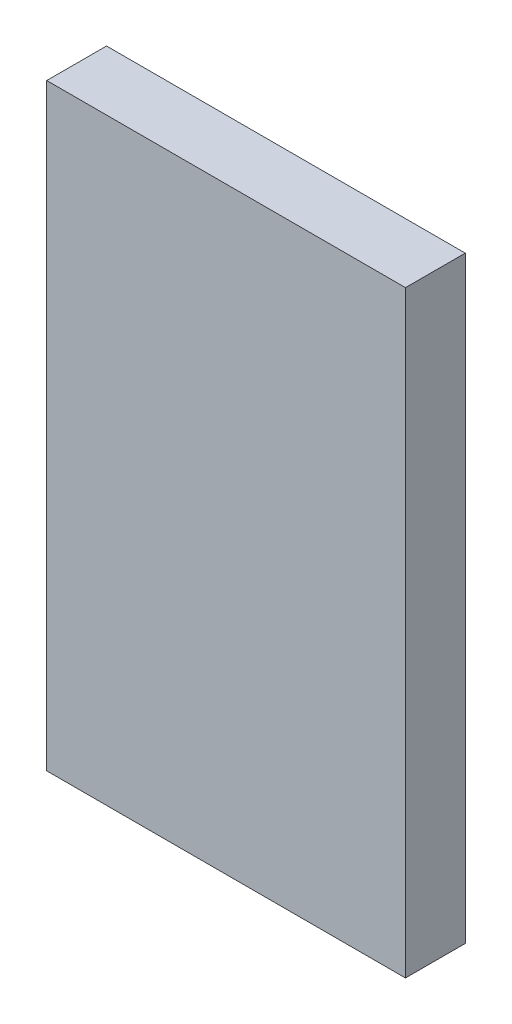
SolidWorks part; units mm, degrees
ref_plane "Спереди" through (0, 0, 0) normal (0, 0, 1) x (1, 0, 0)
ref_plane "Сверху" through (0, 0, 0) normal (0, 1, 0) x (1, 0, 0)
ref_plane "Справа" through (0, 0, 0) normal (1, 0, 0) x (0, 0, -1)
sketch "Эскиз1" plane through (0, 0, 0) normal (0, 0, 1) x (1, 0, 0)
  line L1 (0, 0) -> (90, 0)
  line L2 (0, 0) -> (0, -150)
  line L3 (0, -150) -> (90, -150)
  line L4 (90, 0) -> (90, -150)
  dimension "D1" = 150
  dimension "D2" = 90
extrude "Бобышка-Вытянуть1" add sketch "Эскиз1" along normal blind 15
